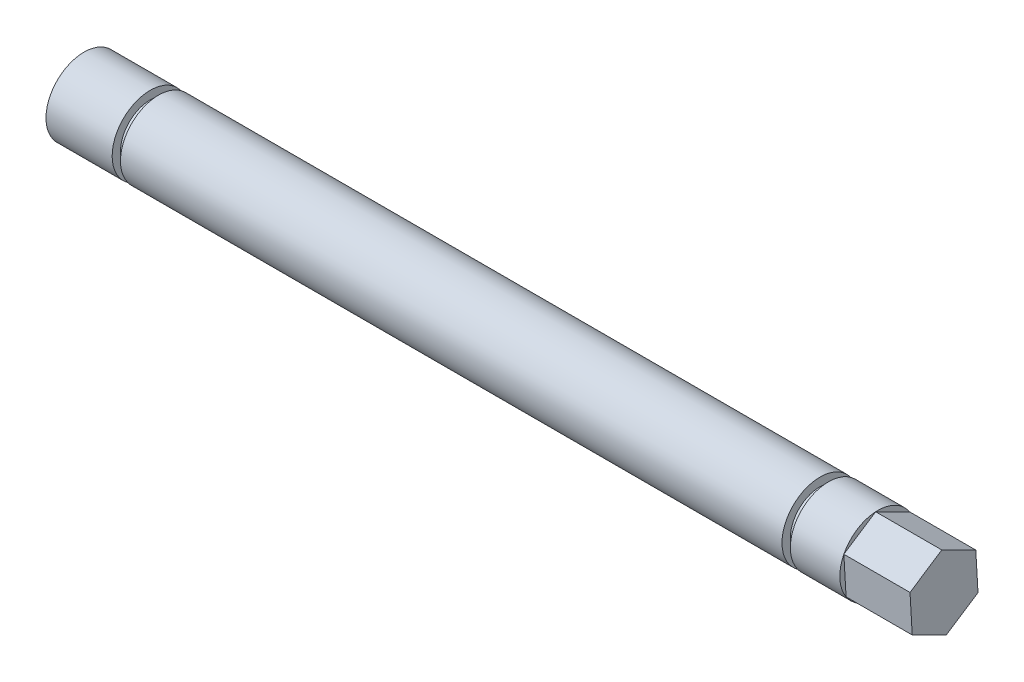
SolidWorks part; units mm, degrees
material "Chrome Stainless Steel"
ref_plane "Front Plane" through (0, 0, 0) normal (0, 0, 1) x (1, 0, 0)
ref_plane "Top Plane" through (0, 0, 0) normal (0, 1, 0) x (1, 0, 0)
ref_plane "Right Plane" through (0, 0, 0) normal (1, 0, 0) x (0, 0, -1)
sketch "Sketch2" plane through (0, 0, 0) normal (1, 0, 0) x (0, 0, -1)
  circle A0 centre (0, 0) radius 7.3025
  dimension "D1" = 14.605
extrude "Boss-Extrude1" add sketch "Sketch2" along normal blind 165.1
sketch "Sketch3" plane through (0, 0, 0) normal (0, 0, 1) x (1, 0, 0)
  line L0 (0, 0) -> (94.6086, 0) construction
  line L1 (1316.2087, 0) -> (-1316.2087, 0) construction
  line L2 (165.1, 7.3025) -> (0, 7.3025) construction
  line L3 (12.7, 7.3025) -> (14.3002, 7.3025)
  line L4 (12.7, 7.3025) -> (12.7, 5.7023)
  line L5 (12.7, 5.7023) -> (14.3002, 5.7023)
  line L6 (14.3002, 7.3025) -> (14.3002, 5.7023)
  dimension "D1" = 94.6086
  dimension "D2" = 12.7
  dimension "D3" = 1.6002
revolve "Cut-Revolve1" cut sketch "Sketch3" angle 360 about L0
ref_plane "Plane1" through (141.3002, 0, 0) normal (-1, 0, 0) x (0, 0, 1)
sketch "Sketch4" plane through (141.3002, 0, 0) normal (-1, 0, 0) x (0, 0, 1)
  circle A0 centre (0, 0) radius 7.3025 construction
  circle A1 centre (0, 0) radius 5.7023 construction
  circle A2 centre (0, 0) radius 7.3025
  circle A3 centre (0, 0) radius 5.7023
extrude "Cut-Extrude1" cut sketch "Sketch4" against normal blind 1.6002 contours A2 | A3
sketch "Sketch5" plane through (165.1, 0, 0) normal (1, 0, 0) x (0, 0, -1)
  line L1 (6.1009, 4.0131) -> (-0.425, 7.2901)
  line L2 (-0.425, 7.2901) -> (-6.5259, 3.277)
  line L3 (-6.5259, 3.277) -> (-6.1009, -4.0131)
  line L4 (-6.1009, -4.0131) -> (0.425, -7.2901)
  line L5 (0.425, -7.2901) -> (6.5259, -3.277)
  line L6 (6.5259, -3.277) -> (6.1009, 4.0131)
  circle A0 centre (0, 0) radius 7.3025 construction
  circle A1 centre (0, 0) radius 7.3025 construction
  point P10 (0.4435, -7.6071)
  dimension "D1" = 14.605
extrude "Cut-Extrude2" cut sketch "Sketch5" against normal blind 12.7 flip side to cut
